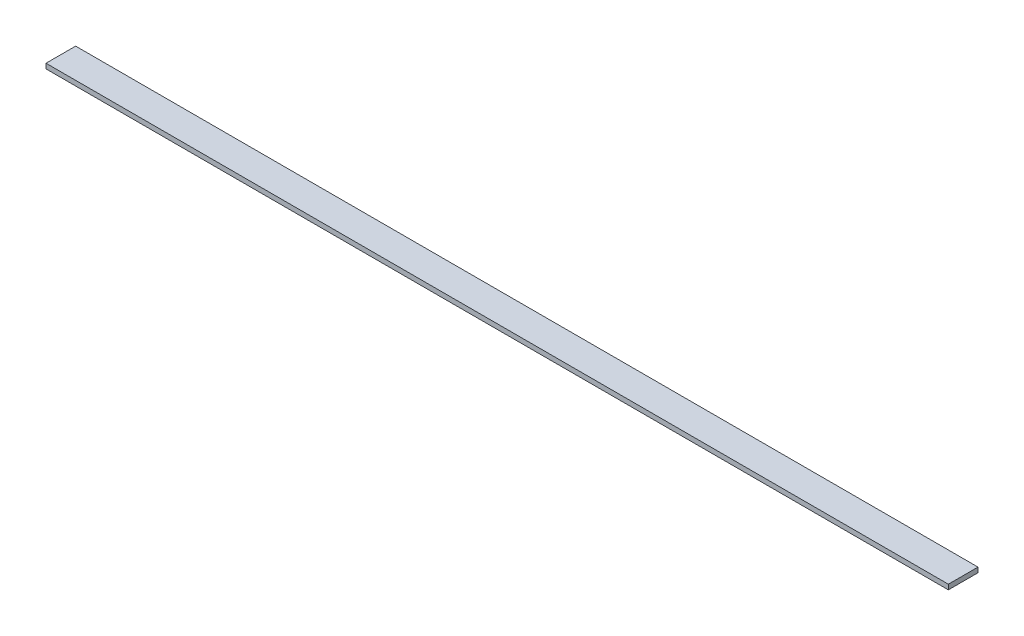
SolidWorks part; units mm, degrees
ref_plane "Alzado" through (0, 0, 0) normal (0, 0, 1) x (1, 0, 0)
ref_plane "Planta" through (0, 0, 0) normal (0, 1, 0) x (1, 0, 0)
ref_plane "Vista lateral" through (0, 0, 0) normal (1, 0, 0) x (0, 0, -1)
sketch "Croquis1" plane through (0, 0, 0) normal (0, 1, 0) x (1, 0, 0)
  line L1 (0, 0) -> (274, 0)
  line L2 (0, 0) -> (0, 9)
  line L3 (0, 9) -> (274, 9)
  line L4 (274, 0) -> (274, 9)
  dimension "D1" = 9
  dimension "D2" = 274
extrude "Saliente-Extruir1" add sketch "Croquis1" along normal blind 1.5
